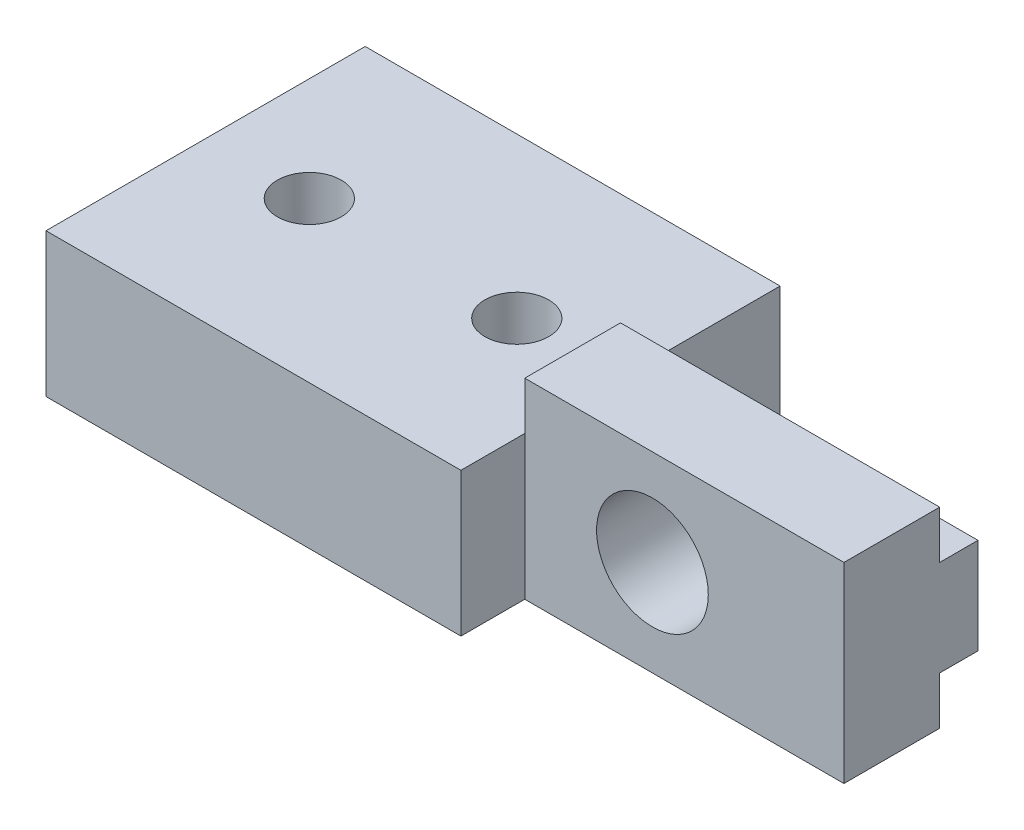
SolidWorks part; units mm, degrees
ref_plane "前视基准面" through (0, 0, 0) normal (0, 0, 1) x (1, 0, 0)
ref_plane "上视基准面" through (0, 0, 0) normal (0, 1, 0) x (1, 0, 0)
ref_plane "右视基准面" through (0, 0, 0) normal (1, 0, 0) x (0, 0, -1)
sketch "草图2" plane through (0, 0, 0) normal (0, 1, 0) x (1, 0, 0)
  line L2 (-3.25, 0) -> (3.25, 0) construction
  line L7 (-6.5, 5) -> (6.5, 5)
  line L8 (-6.5, 5) -> (-6.5, -5)
  line L10 (-6.5, -5) -> (6.5, -5)
  line L11 (6.5, 5) -> (6.5, -5)
  line L12 (-6.5, 5) -> (6.5, -5) construction
  line L13 (-6.5, -5) -> (6.5, 5) construction
  circle A0 centre (-3.25, 0) radius 1
  circle A1 centre (3.25, 0) radius 1
  point P4 (0, 0)
  point P9 (0, 0)
  dimension "D1" = 2
  dimension "D2" = 6.5
  dimension "D3" = 13
  dimension "D4" = 10
extrude "凸台-拉伸1" add sketch "草图2" along normal blind 6
sketch "草图4" plane through (6.5, 0, 11.5) normal (1, 0, 0) x (0, 0, -1)
  line L0 (11.5, 6) -> (11.5, 4.5)
  line L5 (6.5, 6) -> (16.5, 6) construction
  line L6 (11.5, 4.5) -> (12.7, 4.5)
  line L7 (12.7, 4.5) -> (12.7, 1.5)
  line L8 (12.7, 1.5) -> (11.5, 1.5)
  line L9 (11.5, 1.5) -> (11.5, 0)
  line L10 (6.5, 0) -> (16.5, 0) construction
  line L11 (11.5, 0) -> (8.5, 0)
  line L12 (8.5, 0) -> (8.5, 6)
  line L13 (8.5, 6) -> (11.5, 6)
  line L14 (12.7, 3) -> (16.5, 3) construction
  line L15 (16.5, 6) -> (16.5, 0) construction
  dimension "D1" = 3
  dimension "D2" = 1.2
  dimension "D3" = 3
extrude "凸台-拉伸3" add sketch "草图4" along normal blind 10
sketch "草图5" plane through (0, 0, 3) normal (0, 0, 1) x (1, 0, 0)
  line L0 (16.5, 6) -> (16.5, 0) construction
  line L1 (6.5, 6) -> (6.5, 0) construction
  circle A0 centre (10.5, 3) radius 1.75
  point P2 (0, 0)
  point P5 (16.5, 3)
  dimension "D1" = 3.5
  dimension "D2" = 4
extrude "切除-拉伸1" cut sketch "草图5" against normal through all
sketch "草图6" plane through (0, 6, 0) normal (0, 1, 0) x (1, 0, 0)
  line L1 (-6.5, 5) -> (6.5, 5)
  line L2 (-6.5, 5) -> (-6.5, -5)
  line L3 (-6.5, -5) -> (6.5, -5)
  line L4 (6.5, 5) -> (6.5, -5)
extrude "切除-拉伸2" cut sketch "草图6" against normal up to surface (1.5 mm away) up to face at (8.0493, 4.5, -0.6)
